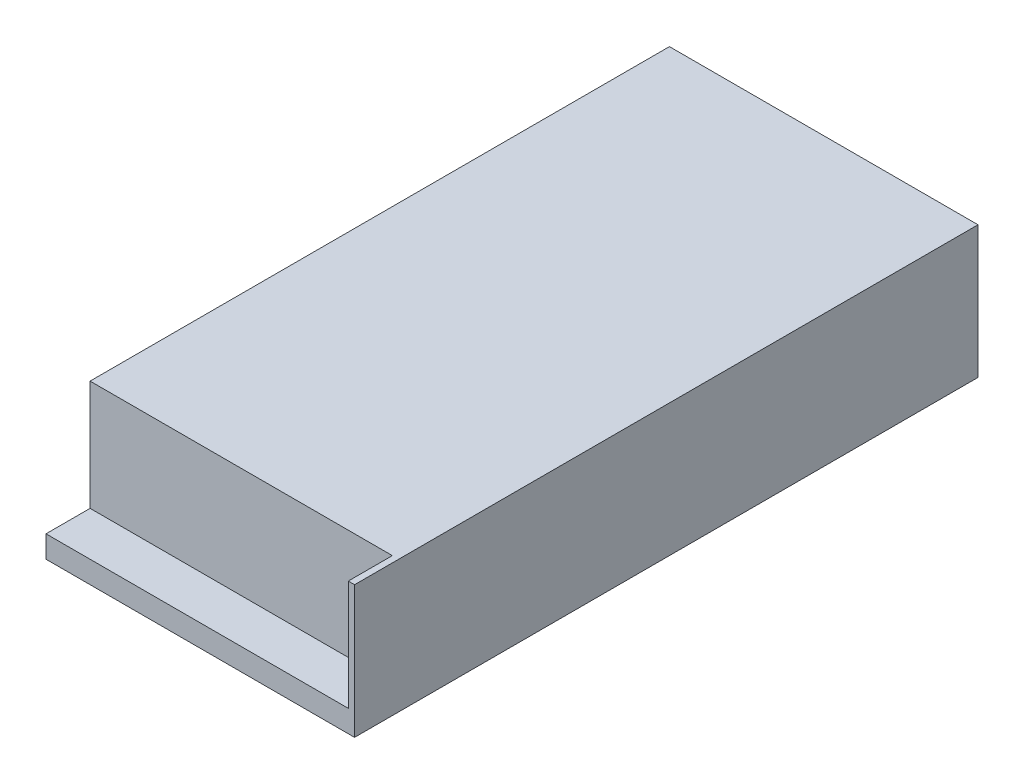
SolidWorks part; units mm, degrees
material "6061 Alloy"
ref_plane "Front Plane" through (0, 0, 0) normal (0, 0, 1) x (1, 0, 0)
ref_plane "Top Plane" through (0, 0, 0) normal (0, 1, 0) x (1, 0, 0)
ref_plane "Right Plane" through (0, 0, 0) normal (1, 0, 0) x (0, 0, -1)
sketch "Sketch1" plane through (0, 0, 0) normal (0, 1, 0) x (1, 0, 0)
  line L1 (-49, -99) -> (49, -99)
  line L2 (-49, -99) -> (-49, 99)
  line L3 (-49, 99) -> (49, 99)
  line L4 (49, -99) -> (49, 99)
  line L5 (-49, -99) -> (49, 99) construction
  line L6 (-49, 99) -> (49, -99) construction
  point P0 (0, 0)
  dimension "D1" = 198
  dimension "D2" = 98
extrude "Boss-Extrude1" add sketch "Sketch1" along normal blind 42
sketch "Sketch2" plane through (0, 42, 0) normal (0, 1, 0) x (1, 0, 0)
  line L0 (49, -99) -> (49, 99) construction
  line L1 (-49, -99) -> (47, -99)
  line L2 (-49, -99) -> (-49, -85)
  line L3 (-49, -85) -> (47, -85)
  line L4 (47, -99) -> (47, -85)
  dimension "D1" = 2
  dimension "D2" = 14
extrude "Cut-Extrude1" cut sketch "Sketch2" against normal blind 35
